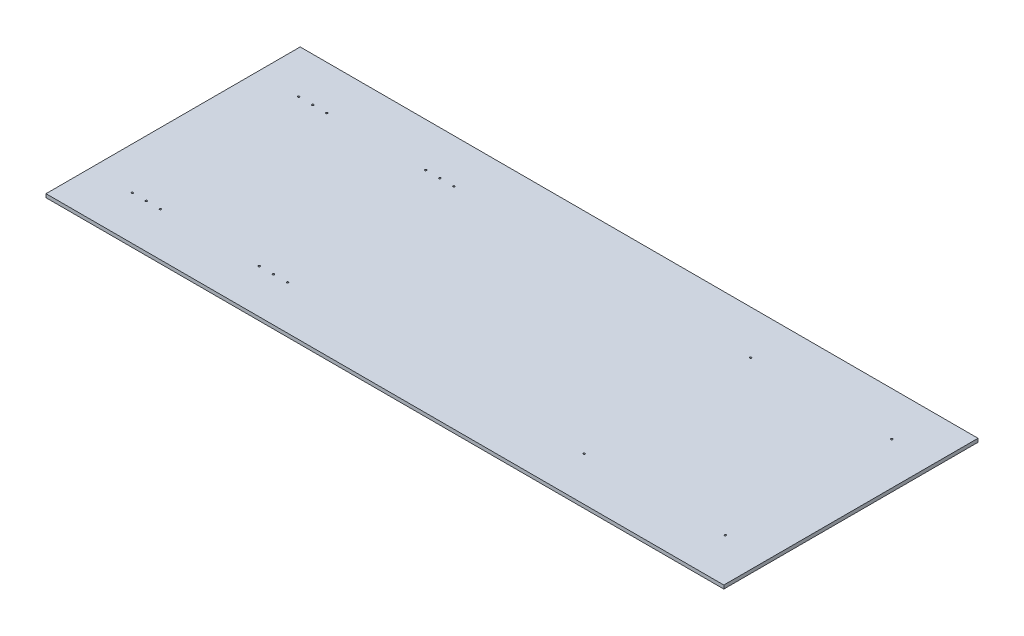
SolidWorks part; units mm, degrees
material "Acrylic (Medium-high impact)"
ref_plane "Front Plane" through (0, 0, 0) normal (0, 0, 1) x (1, 0, 0)
ref_plane "Top Plane" through (0, 0, 0) normal (0, 1, 0) x (1, 0, 0)
ref_plane "Right Plane" through (0, 0, 0) normal (1, 0, 0) x (0, 0, -1)
sketch "Sketch1" plane through (0, 0, 0) normal (0, 1, 0) x (1, 0, 0)
  line L1 (-69.6693, 431.311) -> (1149.5307, 431.311)
  line L2 (-69.6693, 431.311) -> (-69.6693, -25.889)
  line L3 (-69.6693, -25.889) -> (1149.5307, -25.889)
  line L4 (1149.5307, 431.311) -> (1149.5307, -25.889)
  dimension "D1" = 457.2
  dimension "D2" = 1219.2
extrude "Boss-Extrude1" add sketch "Sketch1" along normal blind 6.35
hole_wizard "CSK for #4 Flat Head Machine Screw1" positions "3DSketch1" profile "Sketch2" countersink size "#4" standard "ANSI Inch" end condition through all
sketch3d "3DSketch1"
  line L16 (6.5307, 0, -53.0542) -> (1073.3307, 0, -53.0542)
  line L17 (6.5307, 0, -53.0542) -> (6.5307, 0, -352.3678)
  line L18 (6.5307, 0, -352.3678) -> (1073.3307, 0, -352.3678)
  line L19 (1073.3307, 0, -53.0542) -> (1073.3307, 0, -352.3678)
  line L20 (-69.6693, 0, -431.311) -> (-69.6693, 0, 25.889) construction
  line L21 (1149.5307, 0, 25.889) -> (1149.5307, 0, -431.311) construction
  line L22 (539.9307, 6.35, -431.311) -> (539.9307, 0, -352.3678) construction
  line L23 (1149.5307, 6.35, -431.311) -> (-69.6693, 6.35, -431.311) construction
  line L25 (539.9307, 0, -53.0542) -> (539.9307, 6.35, 25.889) construction
  line L26 (-69.6693, 6.35, 25.889) -> (1149.5307, 6.35, 25.889) construction
  line L28 (1149.5307, 6.35, 25.889) -> (1149.5307, 6.35, -431.311) construction
  line L29 (-69.6693, 6.35, -431.311) -> (-69.6693, 6.35, 25.889) construction
  point P0 (1073.3307, 0, -53.0542)
  point P1 (1073.3307, 0, -352.3678)
  point P3 (819.3918, 0, -352.3678)
  point P5 (819.3918, 0, -53.0542)
  point P7 (6.5307, 0, -53.0542)
  point P9 (235.0645, 0, -53.0542)
  point P11 (235.0645, 0, -352.3678)
  point P13 (6.5307, 0, -352.3678)
  dimension "D1" = 299.3136
  dimension "D2" = 76.2
  dimension "D4" = 330.2
  dimension "D3" = 76.2
  dimension "D5" = 330.2
  dimension "D6" = 304.8
  dimension "D7" = 304.8
sketch "Sketch2" plane through (1073.3307, 0, -53.0542) normal (1, 0, 0) x (0, 0, -1)
  line L0 (0, 0) -> (0, 6.35)
  line L1 (0, 6.35) -> (1.6319, 6.35)
  line L2 (1.6319, 6.35) -> (1.6319, 1.4098)
  line L3 (1.6319, 1.4098) -> (2.8575, 0)
  line L5 (2.8575, 0) -> (0, 0)
  line L6 (-1.6319, 1.4098) -> (-2.8575, 0) construction
  line L11 (0, -6.35) -> (0, 107.95) construction
  dimension "Thru Hole Dia." = 3.2639
  dimension "Thru Hole Depth" = 6.35
  dimension "Near C'Sink Dia." = 5.715
  dimension "Near C'Sink Angle" = 82
hole_wizard "CSK for #4 Flat Head Machine Screw2" positions "3DSketch3" profile "Sketch5" countersink size "#4" standard "ANSI Inch" end condition through all
sketch3d "3DSketch3"
  line L0 (6.5307, 0, -53.0542) -> (346.5086, 0, -53.0542) construction
  line L1 (6.5307, 0, -53.0542) -> (6.5307, 1.4098, -53.0542) construction
  line L3 (6.5307, 0, -352.3678) -> (6.5307, 1.4098, -352.3678) construction
  line L4 (6.5307, 0, -352.3678) -> (301.7085, 0, -352.3678) construction
  circle A0 centre (6.5307, 0, -53.0542) radius 2.8575 construction
  circle A1 centre (235.0645, 0, -53.0542) radius 2.8575 construction
  circle A2 centre (235.0645, 0, -352.3678) radius 2.8575 construction
  circle A3 centre (6.5307, 0, -352.3678) radius 2.8575 construction
  point P0 (31.9307, 0, -53.0542)
  point P2 (57.3307, 0, -53.0542)
  point P4 (260.4645, 0, -53.0542)
  point P6 (285.8645, 0, -53.0542)
  point P8 (260.4645, 0, -352.3678)
  point P10 (285.8645, 0, -352.3678)
  point P12 (31.9307, 0, -352.3678)
  point P14 (57.3307, 0, -352.3678)
  point P19 (6.5307, -2.8575, -53.0542)
  point P22 (235.0645, -2.8575, -53.0542)
  point P25 (235.0645, -2.8575, -352.3678)
  point P28 (6.5307, -2.8575, -352.3678)
  dimension "D4" = 50.8
  dimension "D6" = 50.8
  dimension "D7" = 25.4
  dimension "D1" = 25.4
  dimension "D2" = 50.8
  dimension "D3" = 25.4
  dimension "D5" = 25.4
  dimension "D8" = 50.8
sketch "Sketch5" plane through (31.9307, 0, -53.0542) normal (1, 0, 0) x (0, 0, -1)
  line L0 (0, 0) -> (0, 6.35)
  line L1 (0, 6.35) -> (1.6319, 6.35)
  line L2 (1.6319, 6.35) -> (1.6319, 1.4098)
  line L3 (1.6319, 1.4098) -> (2.8575, 0)
  line L5 (2.8575, 0) -> (0, 0)
  line L6 (-1.6319, 1.4098) -> (-2.8575, 0) construction
  line L11 (0, -6.35) -> (0, 107.95) construction
  dimension "Thru Hole Dia." = 3.2639
  dimension "Thru Hole Depth" = 6.35
  dimension "Near C'Sink Dia." = 5.715
  dimension "Near C'Sink Angle" = 82
